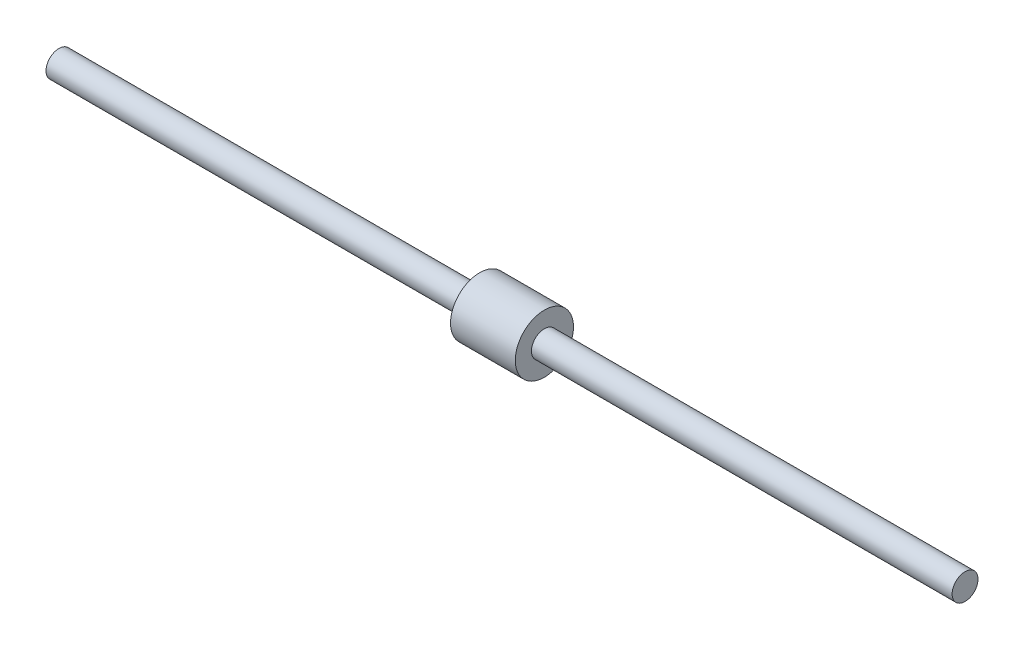
SolidWorks part; units mm, degrees
ref_plane "前视基准面" through (0, 0, 0) normal (0, 0, 1) x (1, 0, 0)
ref_plane "上视基准面" through (0, 0, 0) normal (0, 1, 0) x (1, 0, 0)
ref_plane "右视基准面" through (0, 0, 0) normal (1, 0, 0) x (0, 0, -1)
sketch "草图1" plane through (0, 0, 0) normal (0, 0, 1) x (1, 0, 0)
  line L0 (0, 0) -> (326.6052, 0) construction
  line L1 (0, 0) -> (0, 4)
  line L2 (0, 4) -> (130, 4)
  line L3 (130, 4) -> (130, 9)
  line L4 (130, 9) -> (150, 9)
  line L5 (150, 9) -> (150, 4)
  line L6 (150, 4) -> (280, 4)
  line L7 (280, 4) -> (280, 0)
  line L8 (0, 0) -> (280, 0)
  dimension "D1" = 4
  dimension "D2" = 20
  dimension "D3" = 130
  dimension "D4" = 130
  dimension "D5" = 4
  dimension "D6" = 9
revolve "旋转1" add sketch "草图1" angle 360 about L0
